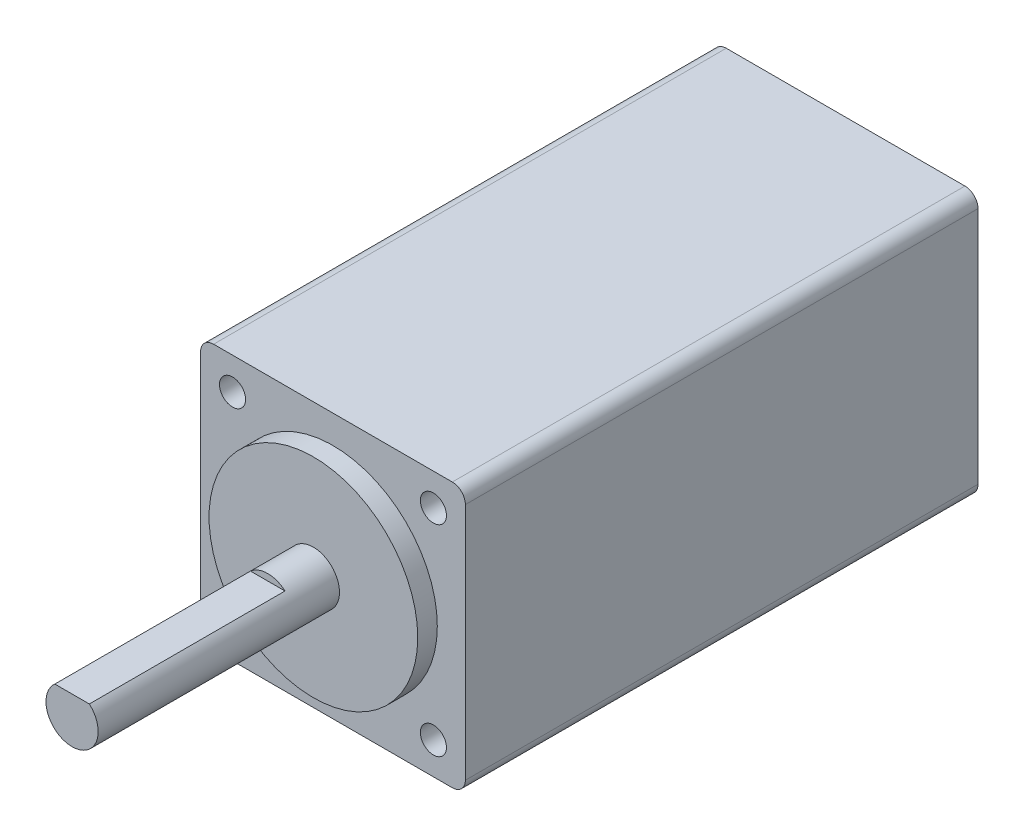
SolidWorks part; units mm, degrees
ref_plane "Front Plane" through (0, 0, 0) normal (0, 0, 1) x (1, 0, 0)
ref_plane "Top Plane" through (0, 0, 0) normal (0, 1, 0) x (1, 0, 0)
ref_plane "Right Plane" through (0, 0, 0) normal (1, 0, 0) x (0, 0, -1)
sketch "Sketch1" plane through (0, 0, 0) normal (0, 0, 1) x (1, 0, 0)
  line L1 (10.15, 10.15) -> (-10.15, 10.15)
  line L2 (10.15, 10.15) -> (10.15, -10.15)
  line L3 (10.15, -10.15) -> (-10.15, -10.15)
  line L4 (-10.15, 10.15) -> (-10.15, -10.15)
  line L5 (10.15, 10.15) -> (-10.15, -10.15) construction
  line L6 (10.15, -10.15) -> (-10.15, 10.15) construction
  point P0 (0, 0)
  dimension "D1" = 20.3
extrude "Boss-Extrude1" add sketch "Sketch1" along normal blind 39.3
fillet "Fillet1" radius 1 4 edges at (10.15, -10.15, 19.65) (-10.15, -10.15, 19.65) (-10.15, 10.15, 19.65) (10.15, 10.15, 19.65)
sketch "Sketch2" plane through (0, 0, 39.3) normal (0, 0, 1) x (1, 0, 0)
  line L1 (7.7, 7.7) -> (-7.7, 7.7) construction
  line L2 (7.7, 7.7) -> (7.7, -7.7) construction
  line L3 (7.7, -7.7) -> (-7.7, -7.7) construction
  line L4 (-7.7, 7.7) -> (-7.7, -7.7) construction
  line L5 (7.7, 7.7) -> (-7.7, -7.7) construction
  line L6 (7.7, -7.7) -> (-7.7, 7.7) construction
  circle A0 centre (-7.7, 7.7) radius 1
  circle A1 centre (-7.7, -7.7) radius 1
  circle A2 centre (7.7, -7.7) radius 1
  circle A3 centre (7.7, 7.7) radius 1
  point P0 (0, 0)
  dimension "D2" = 2
  dimension "D1" = 15.4
extrude "Cut-Extrude1" cut sketch "Sketch2" against normal blind 2.5
sketch "Sketch3" plane through (0, 0, 39.3) normal (0, 0, 1) x (1, 0, 0)
  circle A0 centre (0, 0) radius 8
  dimension "D1" = 16
extrude "Boss-Extrude2" add sketch "Sketch3" along normal blind 1.5
sketch "Sketch5" plane through (0, 0, 39.3) normal (0, 0, 1) x (1, 0, 0)
  circle A0 centre (0, 0) radius 2
  dimension "D1" = 4
extrude "Boss-Extrude3" add sketch "Sketch5" along normal blind 20
sketch "Sketch6" plane through (0, 0, 59.3) normal (0, 0, 1) x (1, 0, 0)
  line L0 (-1.3229, 1.5) -> (1.3229, 1.5)
  circle A0 centre (0, 0) radius 2 construction
  arc A1 (1.3229, 1.5) -> (-1.3229, 1.5) centre (0, 0) ccw
  point P3 (0, -2)
  dimension "D1" = 3.5
extrude "Cut-Extrude2" cut sketch "Sketch6" against normal blind 15
